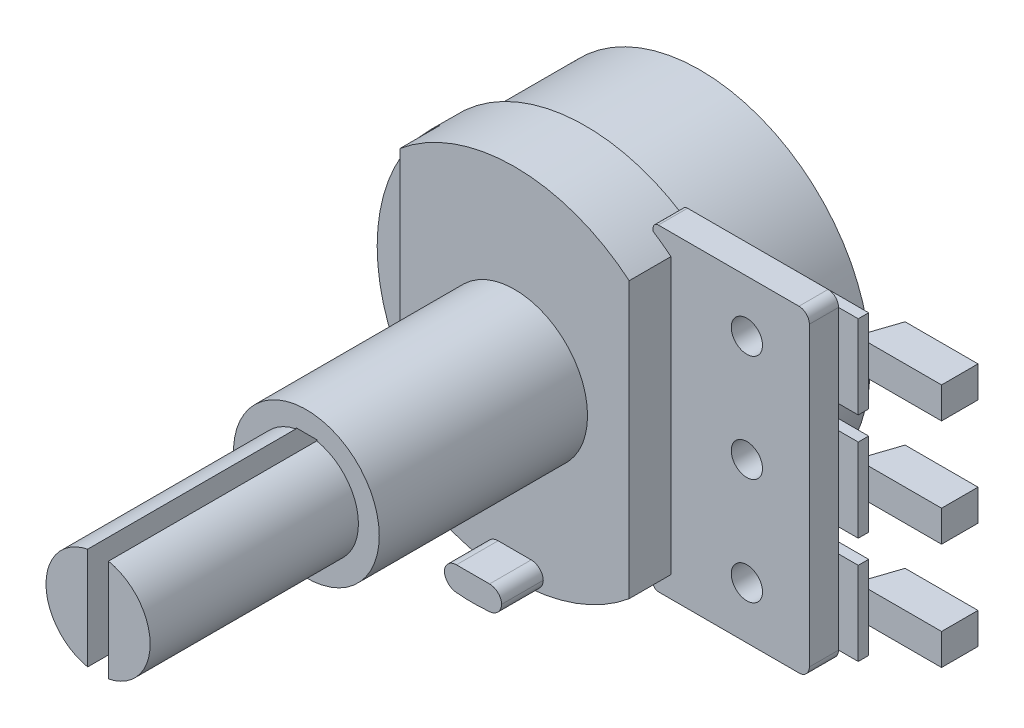
SolidWorks part; units mm, degrees
ref_plane "Спереди" through (0, 0, 0) normal (0, 0, 1) x (1, 0, 0)
ref_plane "Сверху" through (0, 0, 0) normal (0, 1, 0) x (1, 0, 0)
ref_plane "Справа" through (0, 0, 0) normal (1, 0, 0) x (0, 0, -1)
sketch "Эскиз2" plane through (0, 0, 0) normal (0, 0, 1) x (1, 0, 0)
  circle A0 centre (0, 0) radius 8.175
extrude "Бобышка-Вытянуть1" add sketch "Эскиз2" along normal blind 5.5
sketch "Эскиз3" plane through (0, 0, 5.5) normal (0, 0, 1) x (1, 0, 0)
  line L0 (4.65, -7.375) -> (4.65, -7.2345)
  line L1 (4.9, 7.625) -> (11.65, 7.625)
  line L3 (4.9, -7.625) -> (11.65, -7.625)
  line L4 (12.15, 7.125) -> (12.15, -7.125)
  line L5 (0, -50) -> (0, 50) construction
  line L8 (4.65, 7.375) -> (4.65, 7.2345)
  arc A0 (4.65, 7.2345) -> (4.65, -7.2345) centre (0, 0) ccw
  arc A1 (11.65, -7.625) -> (12.15, -7.125) centre (11.65, -7.125) ccw
  arc A2 (12.15, 7.125) -> (11.65, 7.625) centre (11.65, 7.125) ccw
  arc A3 (4.65, -7.375) -> (4.9, -7.625) centre (4.9, -7.375) ccw
  arc A5 (4.65, 7.375) -> (4.9, 7.625) centre (4.9, 7.375) cw
  point P22 (12.15, 0)
  dimension "D2" = 0.5
  dimension "D3" = 7.5
  dimension "D5" = 0.25
  dimension "D6" = 0.25
  dimension "D1" = 15.25
  dimension "D4" = 12.15
extrude "Бобышка-Вытянуть2" add sketch "Эскиз3" along normal blind 1.4
sketch "Эскиз5" plane through (0, 0, 0) normal (0, 0, -1) x (-1, 0, 0)
  line L1 (-1.25, -5.675) -> (1.25, -5.675)
  line L2 (-1.25, -5.675) -> (-1.25, -8.175)
  line L3 (-1.25, -8.175) -> (1.25, -8.175)
  line L4 (1.25, -5.675) -> (1.25, -8.175)
  line L6 (0, 50) -> (0, -50) construction
  circle A1 centre (0, 0) radius 8.175 construction
  point P5 (0, -8.175)
  dimension "D1" = 2.5
  dimension "D2" = 2.5
extrude "Вырез-Вытянуть1" cut sketch "Эскиз5" against normal blind 2.5
sketch "Эскиз6" plane through (0, 0, 6.9) normal (0, 0, 1) x (1, 0, 0)
  line L0 (-5.5, 6.6114) -> (-5.5, -6.6114)
  line L1 (5.5, 6.6114) -> (5.5, -6.6114)
  line L2 (0, -50) -> (0, 50) construction
  arc A0 (5.5, 6.6114) -> (-5.5, 6.6114) centre (0, 0) ccw
  arc A1 (-5.5, -6.6114) -> (5.5, -6.6114) centre (0, 0) ccw
  dimension "D1" = 5.5
  dimension "D3" = 8.6
  dimension "D2" = 5.5
extrude "Бобышка-Вытянуть3" add sketch "Эскиз6" along normal blind 2
sketch "Эскиз7" plane through (0, 0, 8.9) normal (0, 0, 1) x (1, 0, 0)
  circle A0 centre (0, 0) radius 3.5
extrude "Бобышка-Вытянуть4" add sketch "Эскиз7" along normal blind 10
sketch "Эскиз8" plane through (0, 0, 18.9) normal (0, 0, 1) x (1, 0, 0)
  circle A0 centre (0, 0) radius 2.5
extrude "Бобышка-Вытянуть5" add sketch "Эскиз8" along normal blind 10
sketch "Эскиз9" plane through (0, 0, 28.9) normal (0, 0, 1) x (1, 0, 0)
  line L1 (-0.5, 2.5) -> (0.5, 2.5)
  line L2 (-0.5, 2.5) -> (-0.5, -2.5)
  line L3 (-0.5, -2.5) -> (0.5, -2.5)
  line L4 (0.5, 2.5) -> (0.5, -2.5)
  line L5 (0, -50) -> (0, 50) construction
  circle A0 centre (0, 0) radius 2.5 construction
  circle A1 centre (0, 0) radius 2.5 construction
  point P4 (0, 2.5)
  point P9 (0, -2.5)
  dimension "D1" = 1
extrude "Вырез-Вытянуть5" cut sketch "Эскиз9" against normal blind 11.5
sketch "Эскиз12" plane through (0, 0, 5.5) normal (0, 0, -1) x (-1, 0, 0)
  line L0 (-9.15, -2) -> (-13.0958, -2)
  line L1 (-9.15, 7.1259) -> (-13.0958, 7.1259)
  line L3 (-9.15, 3.1259) -> (-13.0958, 3.1259)
  line L4 (-13.0958, 7.1259) -> (-13.0958, 3.1259)
  line L5 (-9.15, 2) -> (-13.0958, 2)
  line L6 (-13.0958, 2) -> (-13.0958, -2)
  line L7 (-13.0958, -3.125) -> (-13.0958, -7.125)
  line L8 (-9.15, -7.125) -> (-13.0958, -7.125)
  line L9 (-9.15, -3.125) -> (-13.0958, -3.125)
  arc A0 (-9.15, -2) -> (-8.0084, -1.6422) centre (-9.15, 0) ccw
  arc A1 (-9.15, -7.125) -> (-9.15, -3.125) centre (-9.15, -5.125) ccw
  arc A2 (-8.0084, 1.6422) -> (-8.0084, -1.6422) centre (0, 0) ccw
  arc A3 (-9.15, 3.1259) -> (-9.15, 7.1259) centre (-9.15, 5.1259) ccw
  arc A4 (-8.0084, 1.6422) -> (-9.15, 2) centre (-9.15, 0) ccw
  point P6 (-9.15, 5.1259)
  point P7 (-9.15, 0)
  point P14 (-9.15, -5.125)
  dimension "D1" = 4
  dimension "D2" = 4
  dimension "D3" = 4
extrude "Бобышка-Вытянуть6" add sketch "Эскиз12" along normal blind 0.5
sketch "Эскиз14" plane through (0, 0, 5) normal (0, 0, -1) x (-1, 0, 0)
  line L1 (-16.5958, 5.8759) -> (-12.5958, 5.8759)
  line L2 (-16.5958, 5.8759) -> (-16.5958, 4.3759)
  line L3 (-16.5958, 4.3759) -> (-12.5958, 4.3759)
  line L4 (-12.5958, 5.8759) -> (-12.5958, 4.3759)
  line L5 (-12.5958, 0.75) -> (-12.5958, -0.75)
  line L6 (-16.5958, 0.75) -> (-16.5958, -0.75)
  line L7 (-16.5958, 0.75) -> (-12.5958, 0.75)
  line L8 (-16.5958, -0.75) -> (-12.5958, -0.75)
  line L9 (-16.5958, -5.875) -> (-12.5958, -5.875)
  line L10 (-16.5958, -4.375) -> (-12.5958, -4.375)
  line L11 (-16.5958, -4.375) -> (-16.5958, -5.875)
  line L12 (-12.5958, -4.375) -> (-12.5958, -5.875)
  dimension "D1" = 1.5
  dimension "D2" = 4
  dimension "D3" = 1.5
  dimension "D4" = 4
  dimension "D5" = 1.5
  dimension "D6" = 4
extrude "Бобышка-Вытянуть7" add sketch "Эскиз14" along normal blind 1.75 separate body
sketch "Эскиз11" plane through (0, 0, 6.9) normal (0, 0, 1) x (1, 0, 0)
  line L3 (11.65, 7.625) -> (4.9, 7.625) construction
  line L6 (12.15, -7.125) -> (12.15, 7.125) construction
  circle A0 centre (9.15, 5.125) radius 0.75
  circle A1 centre (9.15, 0) radius 0.75
  circle A2 centre (9.15, -5.125) radius 0.75
  dimension "D1" = 3
  dimension "D2" = 2.5
  dimension "D4" = 3
  dimension "D5" = 3
extrude "Вырез-Вытянуть6" cut sketch "Эскиз11" against normal up to next
chamfer "Фаска1" distance 1.5 distance2 0.5 1 edges at (12.5958, 5.1259, 3.25)
chamfer "Фаска2" distance 1.5 distance2 0.5 1 edges at (12.5958, 0, 3.25)
chamfer "Фаска3" distance 1.5 distance2 0.5 1 edges at (12.5958, -5.125, 3.25)
sketch "Эскиз15" plane through (0, 0, 8.9) normal (0, 0, 1) x (1, 0, 0)
  line L0 (-0.795, -7.35) -> (0.795, -7.35)
  line L4 (0, -50) -> (0, 50) construction
  line L5 (-1.375, -7.93) -> (-1.375, -7.8843)
  line L6 (1.375, -7.93) -> (1.375, -7.8843)
  arc A1 (-0.8141, -8.5015) -> (0.8141, -8.5015) centre (0, 0) ccw
  arc A3 (-1.375, -7.8843) -> (-0.8141, -8.5015) centre (-0.755, -7.8843) ccw
  arc A4 (1.375, -7.8843) -> (0.8141, -8.5015) centre (0.755, -7.8843) cw
  arc A5 (1.375, -7.93) -> (0.795, -7.35) centre (0.795, -7.93) ccw
  arc A6 (-1.375, -7.93) -> (-0.795, -7.35) centre (-0.795, -7.93) cw
  point P11 (0, -7.35)
  point P15 (1.375, -7.35)
  point P18 (-1.375, -7.35)
  dimension "D1" = 7.35
  dimension "D3" = 0.62
  dimension "D4" = 0.62
  dimension "D5" = 0.58
  dimension "D2" = 2.75
extrude "Бобышка-Вытянуть8" add sketch "Эскиз15" along normal blind 2 contours A6 A3 A1 A4 A5 L0
